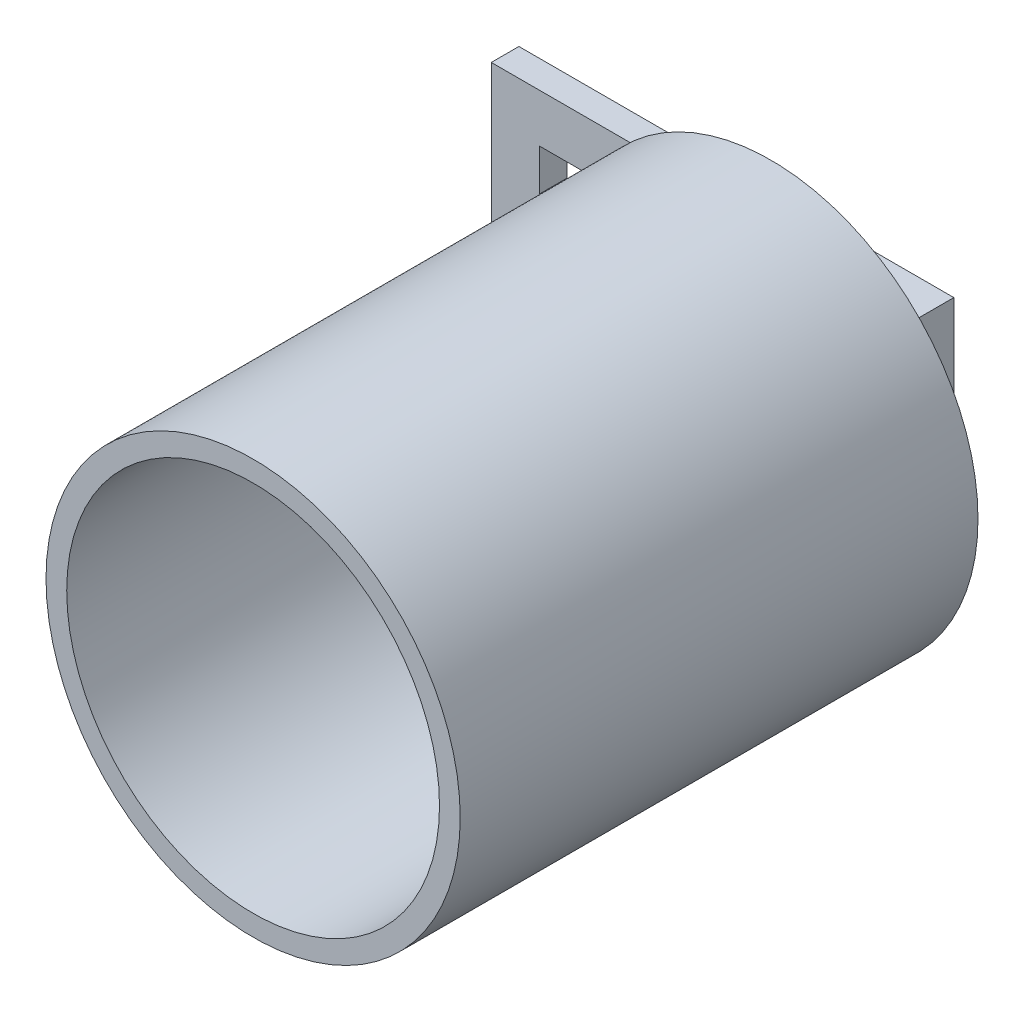
SolidWorks part; units mm, degrees
ref_plane "Plan de face" through (0, 0, 0) normal (0, 0, 1) x (1, 0, 0)
ref_plane "Plan de dessus" through (0, 0, 0) normal (0, 1, 0) x (1, 0, 0)
ref_plane "Plan de droite" through (0, 0, 0) normal (1, 0, 0) x (0, 0, -1)
sketch "Esquisse1" plane through (0, 0, 0) normal (0, 0, 1) x (1, 0, 0)
  circle A0 centre (0, 0) radius 30
  dimension "D1" = 60
extrude "Boss.-Extru.1" add sketch "Esquisse1" along normal blind 75 contours A0
sketch "Esquisse2" plane through (0, 0, 75) normal (0, 0, 1) x (1, 0, 0)
  circle A0 centre (0, 0) radius 27
  circle A1 centre (0, 0) radius 30 construction
  dimension "D1" = 3
extrude "Enlèv. mat.-Extru.1" cut sketch "Esquisse2" against normal blind 70 contours A0
sketch "Esquisse3" plane through (0, 0, 0) normal (0, 0, -1) x (-1, 0, 0)
  line L1 (-10.5, -10) -> (10.5, -10)
  line L2 (-10.5, -10) -> (-10.5, 10)
  line L3 (-10.5, 10) -> (10.5, 10)
  line L4 (10.5, -10) -> (10.5, 10)
  line L5 (-10.5, -10) -> (10.5, 10) construction
  line L6 (-10.5, 10) -> (10.5, -10) construction
  point P0 (0, 0)
  dimension "D1" = 20
  dimension "D2" = 21
extrude "Boss.-Extru.2" add sketch "Esquisse3" along normal blind 16
sketch "Esquisse4" plane through (-10.5, 0, 0) normal (-1, 0, 0) x (0, 0, 1)
  line L0 (0, -10) -> (0, 10) construction
  line L1 (-16, 10) -> (-12, 10)
  line L2 (-16, 10) -> (-16, -10)
  line L3 (-16, -10) -> (-12, -10)
  line L4 (-12, 10) -> (-12, -10)
  line L5 (-16, 10) -> (-12, -10) construction
  line L6 (-16, -10) -> (-12, 10) construction
  line L7 (-16, 10) -> (0, 10) construction
  line L8 (-16, -10) -> (0, -10) construction
  point P0 (-14, 0)
  dimension "D1" = 12
  dimension "D2" = 4
  dimension "D3" = 0
  dimension "D4" = 0
extrude "Boss.-Extru.3" add sketch "Esquisse4" along normal blind 42
sketch "Esquisse5" plane through (0, 0, -16) normal (0, 0, -1) x (-1, 0, 0)
  line L0 (-10.5, -10) -> (52.5, -10) construction
  line L1 (35.5, -3) -> (45.5, -3)
  line L2 (35.5, -3) -> (35.5, 3)
  line L3 (35.5, 3) -> (45.5, 3)
  line L4 (45.5, -3) -> (45.5, 3)
  line L5 (35.5, -3) -> (45.5, 3) construction
  line L6 (35.5, 3) -> (45.5, -3) construction
  line L8 (52.5, 10) -> (52.5, -10) construction
  point P0 (40.5, 0)
  dimension "D1" = 6
  dimension "D2" = 10
  dimension "D3" = 7
  dimension "D4" = 7
extrude "Enlèv. mat.-Extru.2" cut sketch "Esquisse5" against normal up to next
equation "\"taille\"= 3mm"
